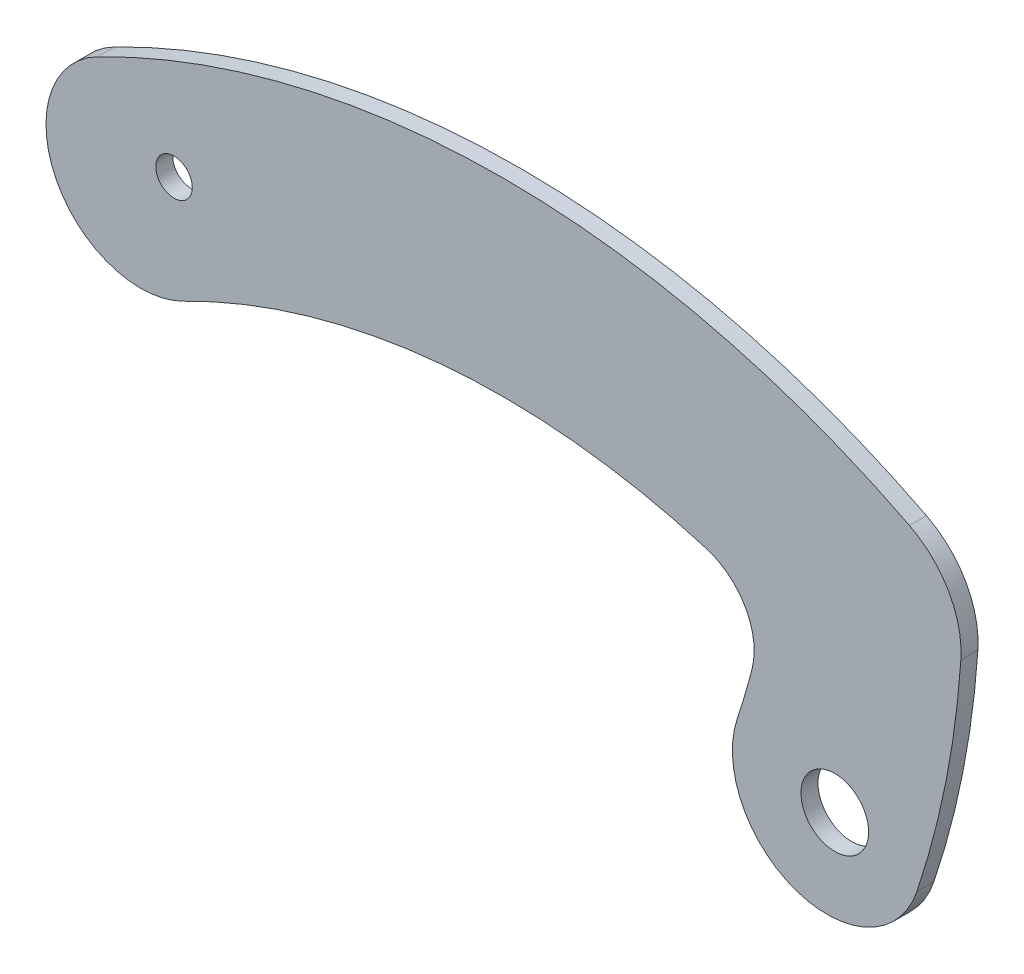
SolidWorks part; units mm, degrees
ref_plane "Front Plane" through (0, 0, 0) normal (0, 0, 1) x (1, 0, 0)
ref_plane "Top Plane" through (0, 0, 0) normal (0, 1, 0) x (1, 0, 0)
ref_plane "Right Plane" through (0, 0, 0) normal (1, 0, 0) x (0, 0, -1)
sketch "Sketch1" plane through (0, 0, 0) normal (0, 0, 1) x (1, 0, 0)
  line L84 (-8.0971, 15.8327) -> (8.0971, -15.8327) construction
  line L85 (144.3983, 15.8327) -> (128.2041, -15.8327) construction
  line L86 (0, 0) -> (136.3012, 0) construction
  arc A81 (-8.0971, 15.8327) -> (144.3983, 15.8327) centre (68.1506, -133.2589) cw
  arc A82 (8.0971, -15.8327) -> (128.2041, -15.8327) centre (68.1506, -133.2589) cw
  arc A84 (-8.0971, 15.8327) -> (8.0971, -15.8327) centre (0, 0) ccw
  arc A85 (144.3983, 15.8327) -> (128.2041, -15.8327) centre (136.3012, 0) cw
  dimension "D10" = 131.8914
  dimension "D11" = 35.5662
  dimension "D12" = 136.3012
extrude "Boss-Extrude1" add sketch "Sketch1" along normal blind 3.2004
sketch "Sketch2" plane through (0, 0, 3.2004) normal (0, 0, 1) x (1, 0, 0)
  line L0 (-8.0971, 15.8327) -> (8.0971, -15.8327) construction
  line L13 (6.2618, 3.4378) -> (6.6133, 2.5127) construction
  line L30 (6.6133, 2.5127) -> (0, 0) construction
  line L31 (37.5312, 20.6671) -> (41.0829, 11.3191) construction
  line L32 (-9.6763, 2.7309) -> (-6.1245, -6.6171) construction
  line L33 (39.307, 15.9931) -> (-7.9004, -1.9431) construction
  circle A14 centre (41.0829, 11.3191) radius 1.7272 construction
  circle A15 centre (-9.6763, 2.7309) radius 1.7272 construction
  circle A16 centre (-6.1245, -6.6171) radius 1.7272 construction
  circle A17 centre (37.5312, 20.6671) radius 1.7272 construction
  circle A18 centre (6.2618, 3.4378) radius 3.429
  point P4 (6.2618, 3.4378)
  dimension "D2" = 96.282
  dimension "D10" = 6.858
  dimension "D9" = 3.4544
  dimension "D11" = 50.5
  dimension "D12" = 15.15
  dimension "D13" = 10
  dimension "D14" = 7.0746
  dimension "D15" = 0.9896
extrude "Cut-Extrude1" cut sketch "Sketch2" against normal up to surface (3.2004 mm away) up to face at (68.1506, 4.1592, 0)
sketch "Sketch3" plane through (0, 0, 3.2004) normal (0, 0, 1) x (1, 0, 0)
  line L0 (136.3012, 0) -> (128.9162, -37.3774) construction
  line L1 (154.0439, -1.1985) -> (118.5586, 1.1985) construction
  line L5 (144.3983, 15.8327) -> (128.2041, -15.8327) construction
  line L6 (0, 0) -> (136.3012, 0) construction
  line L7 (112.0509, -31.7381) -> (145.7814, -43.0168) construction
  arc A0 (118.5586, 1.1985) -> (154.0439, -1.1985) centre (136.3012, 0) cw
  arc A2 (112.0509, -31.7381) -> (145.7814, -43.0168) centre (128.9162, -37.3774) ccw
  arc A3 (118.5586, 1.1985) -> (112.0509, -31.7381) centre (-13.033, 10.0872) cw
  arc A4 (154.0439, -1.1985) -> (145.7814, -43.0168) centre (-13.033, 10.0872) cw
  dimension "D1" = 131.8914
  dimension "D2" = 38.1
  dimension "D3" = 78.823
extrude "Boss-Extrude2" add sketch "Sketch3" against normal up to surface (3.2004 mm away) up to face at (2.8328, 3.4378, 0)
sketch "Sketch4" plane through (0, 0, 3.2004) normal (0, 0, 1) x (1, 0, 0)
  line L0 (112.0509, -31.7381) -> (145.7814, -43.0168) construction
  circle A0 centre (130.3615, -37.8607) radius 6.35
  dimension "D10" = 12.7
  dimension "D2" = 1.524
extrude "Cut-Extrude2" cut sketch "Sketch4" against normal up to surface (3.2004 mm away) up to face at (93.6811, -9.2345, 0)
fillet "Fillet1" radius 12.7 1 edges at (117.1902, -10.8234, 1.6002)
